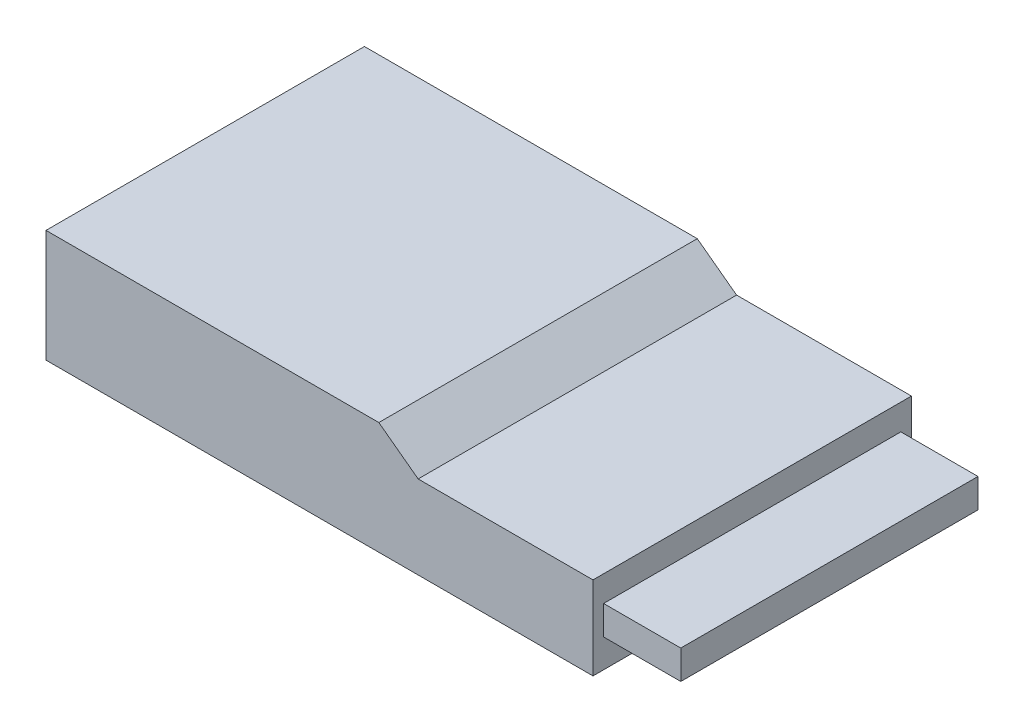
SolidWorks part; units mm, degrees
ref_plane "Front Plane" through (0, 0, 0) normal (0, 0, 1) x (1, 0, 0)
ref_plane "Top Plane" through (0, 0, 0) normal (0, 1, 0) x (1, 0, 0)
ref_plane "Right Plane" through (0, 0, 0) normal (1, 0, 0) x (0, 0, -1)
sketch "Sketch1" plane through (0, 0, 0) normal (0, 1, 0) x (1, 0, 0)
  line L1 (-10.95, 6.375) -> (10.95, 6.375)
  line L2 (-10.95, 6.375) -> (-10.95, -6.375)
  line L3 (-10.95, -6.375) -> (10.95, -6.375)
  line L4 (10.95, 6.375) -> (10.95, -6.375)
  line L5 (-10.95, 6.375) -> (10.95, -6.375) construction
  line L6 (-10.95, -6.375) -> (10.95, 6.375) construction
  point P0 (0, 0)
  dimension "D1" = 12.75
  dimension "D2" = 21.9
extrude "Boss-Extrude1" add sketch "Sketch1" along normal blind 4.5
sketch "Sketch3" plane through (10.95, 0, 0) normal (1, 0, 0) x (0, 0, -1)
  line L1 (-5.95, 1.14) -> (-5.95, 2.3)
  line L2 (-5.95, 2.3) -> (5.95, 2.3)
  line L3 (5.95, 2.3) -> (5.95, 1.14)
  line L4 (5.95, 1.14) -> (-5.95, 1.14)
  line L6 (-6.375, 0) -> (6.375, 0) construction
  point P3 (0, 0)
  point P10 (0, 0)
  point P11 (0, 0)
  point P12 (0, 2.3)
  point P14 (0, 0)
  point P15 (0, 0)
  point P16 (-6.375, 4.5169)
  point P17 (-6.375, -1.9708)
  dimension "D1" = 11.9
  dimension "D2" = 1.16
  dimension "D3" = 2.3
extrude "Boss-Extrude2" add sketch "Sketch3" along normal blind 3.09
sketch "Sketch4" plane through (0, 0, 6.375) normal (0, 0, 1) x (1, 0, 0)
  line L0 (10.95, 3.3308) -> (3.95, 3.3308)
  line L1 (10.95, 4.5) -> (10.95, 0) construction
  line L2 (3.95, 3.3308) -> (2.3759, 4.5)
  line L3 (-10.95, 4.5) -> (10.95, 4.5) construction
  line L4 (2.3759, 4.5) -> (10.95, 4.5)
  line L5 (10.95, 4.5) -> (10.95, 3.3308)
  dimension "D1" = 7
  dimension "D2" = 1.1692
  dimension "D3" = 1.9608
extrude "Cut-Extrude1" cut sketch "Sketch4" against normal blind 13
